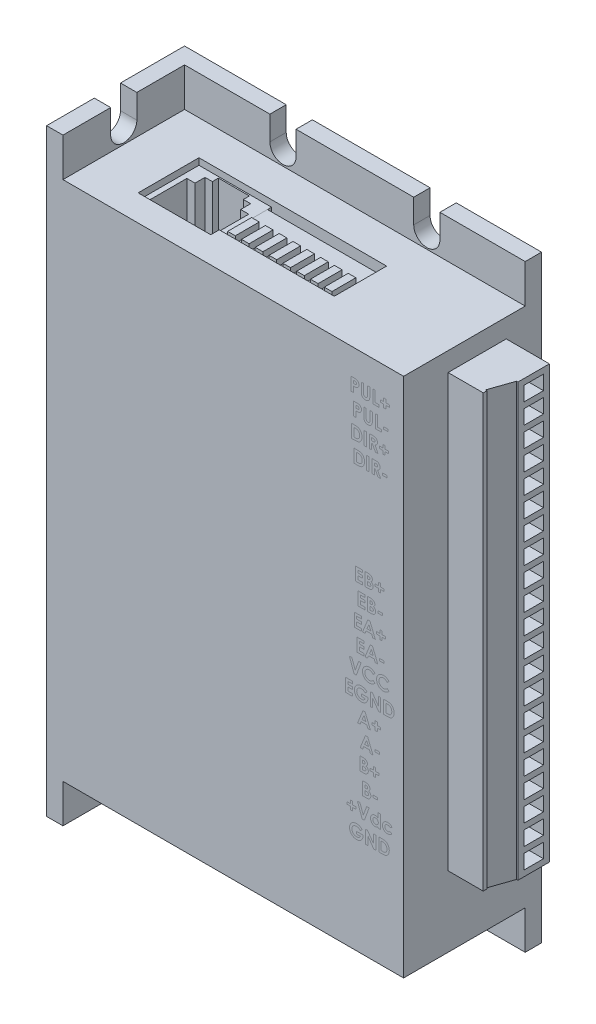
SolidWorks part; units mm, degrees
ref_plane "Front Plane" through (0, 0, 0) normal (0, 0, 1) x (1, 0, 0)
ref_plane "Top Plane" through (0, 0, 0) normal (0, 1, 0) x (1, 0, 0)
ref_plane "Right Plane" through (0, 0, 0) normal (1, 0, 0) x (0, 0, -1)
sketch "Sketch1" plane through (0, 0, 0) normal (0, 0, 1) x (1, 0, 0)
  line L1 (-34.671, 58.1025) -> (34.671, 58.1025)
  line L2 (-34.671, 58.1025) -> (-34.671, -58.1025)
  line L3 (-34.671, -58.1025) -> (34.671, -58.1025)
  line L4 (34.671, 58.1025) -> (34.671, -58.1025)
  line L5 (-34.671, 58.1025) -> (34.671, -58.1025) construction
  line L6 (-34.671, -58.1025) -> (34.671, 58.1025) construction
  point P0 (0, 0)
  dimension "D1" = 69.342
  dimension "D2" = 116.205
extrude "Boss-Extrude1" add sketch "Sketch1" along normal blind 26.797
sketch "Sketch2" plane through (0, 0, 26.797) normal (0, 0, 1) x (1, 0, 0)
  line L0 (34.671, 58.1025) -> (-34.671, 58.1025) construction
  line L1 (-31.496, 58.1025) -> (34.671, 58.1025)
  line L2 (-31.496, 58.1025) -> (-31.496, 50.6095)
  line L3 (-31.496, 50.6095) -> (34.671, 50.6095)
  line L4 (34.671, 58.1025) -> (34.671, 50.6095)
  line L5 (34.671, -58.1025) -> (34.671, 58.1025) construction
  line L6 (-34.671, -58.1025) -> (34.671, -58.1025) construction
  line L7 (-31.496, -58.1025) -> (34.671, -58.1025)
  line L8 (-31.496, -58.1025) -> (-31.496, -50.6095)
  line L9 (-31.496, -50.6095) -> (34.671, -50.6095)
  line L10 (34.671, -58.1025) -> (34.671, -50.6095)
  line L11 (-34.671, 58.1025) -> (-34.671, -58.1025) construction
  dimension "D1" = 7.493
  dimension "D2" = 3.175
extrude "Cut-Extrude1" cut sketch "Sketch2" against normal offset from surface (23.622 mm away) 3.175 up to face at (0, 0, 0)
sketch "Sketch3" plane through (-31.496, 0, 0) normal (1, 0, 0) x (0, 0, -1)
  line L0 (-14.986, 62.7642) -> (-14.986, 53.4408) construction
  line L1 (-3.175, 58.1025) -> (-26.797, 58.1025) construction
  line L2 (-12.446, 62.7642) -> (-12.446, 53.4408)
  line L3 (-17.526, 62.7642) -> (-17.526, 53.4408)
  line L4 (0, 0) -> (-26.797, 0) construction
  line L5 (-26.797, -50.6095) -> (-26.797, 50.6095) construction
  line L6 (-14.986, -62.7642) -> (-14.986, -53.4408) construction
  line L7 (-12.446, -62.7642) -> (-12.446, -53.4408)
  line L8 (-17.526, -62.7642) -> (-17.526, -53.4408)
  arc A0 (-12.446, 62.7642) -> (-17.526, 62.7642) centre (-14.986, 62.7642) ccw
  arc A1 (-17.526, 53.4408) -> (-12.446, 53.4408) centre (-14.986, 53.4408) ccw
  arc A2 (-12.446, -62.7642) -> (-17.526, -62.7642) centre (-14.986, -62.7642) cw
  arc A3 (-17.526, -53.4408) -> (-12.446, -53.4408) centre (-14.986, -53.4408) cw
  point P4 (-14.986, 58.1025)
  point P16 (-14.986, -58.1025)
  dimension "D1" = 5.08
  dimension "D2" = 4.6617
extrude "Cut-Extrude2" cut sketch "Sketch3" against normal through all
sketch "Sketch4" plane through (0, 0, 3.175) normal (0, 0, 1) x (1, 0, 0)
  line L0 (15.5575, 58.1025) -> (-12.3825, 58.1025) construction
  line L1 (-31.496, 58.1025) -> (34.671, 58.1025) construction
  line L2 (-12.3825, 62.7634) -> (-12.3825, 53.4416) construction
  line L3 (-9.8425, 62.7634) -> (-9.8425, 53.4416)
  line L4 (-14.9225, 62.7634) -> (-14.9225, 53.4416)
  line L5 (1.5875, 58.1025) -> (1.5875, -58.1025) construction
  line L6 (34.671, -58.1025) -> (-31.496, -58.1025) construction
  line L7 (1.5875, 0) -> (34.671, 0) construction
  line L8 (34.671, -50.6095) -> (34.671, 50.6095) construction
  line L9 (15.5575, 62.7634) -> (15.5575, 53.4416) construction
  line L10 (13.0175, 62.7634) -> (13.0175, 53.4416)
  line L11 (18.0975, 62.7634) -> (18.0975, 53.4416)
  line L12 (15.5575, -62.7634) -> (15.5575, -53.4416) construction
  line L13 (13.0175, -62.7634) -> (13.0175, -53.4416)
  line L14 (18.0975, -62.7634) -> (18.0975, -53.4416)
  line L15 (-12.3825, -62.7634) -> (-12.3825, -53.4416) construction
  line L16 (-9.8425, -62.7634) -> (-9.8425, -53.4416)
  line L17 (-14.9225, -62.7634) -> (-14.9225, -53.4416)
  arc A0 (-9.8425, 62.7634) -> (-14.9225, 62.7634) centre (-12.3825, 62.7634) ccw
  arc A1 (-14.9225, 53.4416) -> (-9.8425, 53.4416) centre (-12.3825, 53.4416) ccw
  arc A2 (13.0175, 62.7634) -> (18.0975, 62.7634) centre (15.5575, 62.7634) cw
  arc A3 (18.0975, 53.4416) -> (13.0175, 53.4416) centre (15.5575, 53.4416) cw
  arc A4 (13.0175, -62.7634) -> (18.0975, -62.7634) centre (15.5575, -62.7634) ccw
  arc A5 (18.0975, -53.4416) -> (13.0175, -53.4416) centre (15.5575, -53.4416) ccw
  arc A6 (-9.8425, -62.7634) -> (-14.9225, -62.7634) centre (-12.3825, -62.7634) cw
  arc A7 (-14.9225, -53.4416) -> (-9.8425, -53.4416) centre (-12.3825, -53.4416) cw
  point P5 (1.5875, 58.1025)
  point P7 (-12.3825, 58.1025)
  point P22 (15.5575, 58.1025)
  point P29 (15.5575, -58.1025)
  point P36 (-12.3825, -58.1025)
  dimension "D1" = 4.6609
  dimension "D2" = 5.08
  dimension "D3" = 27.94
extrude "Cut-Extrude3" cut sketch "Sketch4" against normal through all
sketch "Sketch5" plane through (0, 50.6095, 0) normal (0, 1, 0) x (1, 0, 0)
  line L0 (-34.671, -12.446) -> (-34.671, 0) construction
  line L1 (-21.971, -9.906) -> (-7.874, -9.906)
  line L2 (-21.971, -9.906) -> (-21.971, -21.717)
  line L3 (-21.971, -21.717) -> (-7.874, -21.717)
  line L4 (-7.874, -9.906) -> (-7.874, -21.717)
  line L5 (-31.496, -26.797) -> (34.671, -26.797) construction
  dimension "D1" = 12.7
  dimension "D2" = 11.811
  dimension "D3" = 14.097
  dimension "D4" = 5.08
extrude "Cut-Extrude4" cut sketch "Sketch5" against normal blind 12.7
sketch "Sketch6" plane through (0, 50.6095, 0) normal (0, 1, 0) x (1, 0, 0)
  line L1 (-7.874, -9.906) -> (14.478, -9.906)
  line L2 (-7.874, -9.906) -> (-7.874, -20.066)
  line L3 (-7.874, -20.066) -> (14.478, -20.066)
  line L4 (14.478, -9.906) -> (14.478, -20.066)
  dimension "D1" = 22.352
  dimension "D2" = 10.16
extrude "Cut-Extrude5" cut sketch "Sketch6" against normal blind 2.54
sketch "Sketch7" plane through (0, 48.0695, 0) normal (0, 1, 0) x (1, 0, 0)
  line L0 (-7.874, -21.717) -> (-7.874, -9.906) construction
  line L1 (-7.874, -10.7001) -> (14.478, -10.7001)
  line L2 (-7.874, -10.7001) -> (-7.874, -20.066)
  line L3 (-7.874, -20.066) -> (14.478, -20.066)
  line L4 (14.478, -10.7001) -> (14.478, -20.066)
extrude "Boss-Extrude2" add sketch "Sketch7" along normal blind 1.27 separate body
sketch "Sketch8" plane through (0, 49.3395, 0) normal (0, 1, 0) x (1, 0, 0)
  line L0 (-4.119, -14.8518) -> (-2.6319, -14.8518)
  line L1 (-6.8001, -14.8518) -> (-5.313, -14.8518)
  line L2 (-6.8001, -14.8518) -> (-6.8001, -19.5049)
  line L3 (-6.8001, -19.5049) -> (-5.313, -19.5049)
  line L4 (-5.313, -14.8518) -> (-5.313, -19.5049)
  line L5 (-2.6319, -14.8518) -> (-2.6319, -19.5049)
  line L6 (-4.119, -19.5049) -> (-2.6319, -19.5049)
  line L7 (-4.119, -14.8518) -> (-4.119, -19.5049)
  line L8 (-1.4379, -14.8518) -> (0.0493, -14.8518)
  line L9 (0.0493, -14.8518) -> (0.0493, -19.5049)
  line L10 (-1.4379, -19.5049) -> (0.0493, -19.5049)
  line L11 (-1.4379, -14.8518) -> (-1.4379, -19.5049)
  line L12 (1.2432, -14.8518) -> (2.7304, -14.8518)
  line L13 (2.7304, -14.8518) -> (2.7304, -19.5049)
  line L14 (1.2432, -19.5049) -> (2.7304, -19.5049)
  line L15 (1.2432, -14.8518) -> (1.2432, -19.5049)
  line L16 (3.9244, -14.8518) -> (5.4115, -14.8518)
  line L17 (5.4115, -14.8518) -> (5.4115, -19.5049)
  line L18 (3.9244, -19.5049) -> (5.4115, -19.5049)
  line L19 (3.9244, -14.8518) -> (3.9244, -19.5049)
  line L20 (6.6055, -14.8518) -> (8.0926, -14.8518)
  line L21 (8.0926, -14.8518) -> (8.0926, -19.5049)
  line L22 (6.6055, -19.5049) -> (8.0926, -19.5049)
  line L23 (6.6055, -14.8518) -> (6.6055, -19.5049)
  line L24 (9.2866, -14.8518) -> (10.7738, -14.8518)
  line L25 (10.7738, -14.8518) -> (10.7738, -19.5049)
  line L26 (9.2866, -19.5049) -> (10.7738, -19.5049)
  line L27 (9.2866, -14.8518) -> (9.2866, -19.5049)
  line L28 (11.9677, -14.8518) -> (13.4549, -14.8518)
  line L29 (13.4549, -14.8518) -> (13.4549, -19.5049)
  line L30 (11.9677, -19.5049) -> (13.4549, -19.5049)
  line L31 (11.9677, -14.8518) -> (11.9677, -19.5049)
  dimension "D1" = 8
extrude "Boss-Extrude3" add sketch "Sketch8" along normal blind 1.27 separate body
sketch "Sketch9" plane through (0, 37.9095, 0) normal (0, 1, 0) x (1, 0, 0)
  line L0 (-14.9225, -9.906) -> (-14.9225, -21.717) construction
  line L1 (-7.874, -9.906) -> (-21.971, -9.906) construction
  line L2 (-21.971, -21.717) -> (-7.874, -21.717) construction
  line L3 (-8.9055, -20.8461) -> (-20.9395, -20.8461)
  line L4 (-20.9395, -20.8461) -> (-20.9395, -13.2906)
  line L5 (-20.9395, -13.2906) -> (-19.3565, -13.2906)
  line L6 (-19.3565, -13.2906) -> (-19.3565, -11.3477)
  line L7 (-19.3565, -11.3477) -> (-17.931, -11.3477)
  line L8 (-17.931, -11.3477) -> (-17.931, -10.169)
  line L9 (-17.931, -10.169) -> (-11.914, -10.169)
  line L10 (-8.9055, -20.8461) -> (-8.9055, -13.2906)
  line L11 (-8.9055, -13.2906) -> (-10.4885, -13.2906)
  line L12 (-10.4885, -13.2906) -> (-10.4885, -11.3477)
  line L13 (-10.4885, -11.3477) -> (-11.914, -11.3477)
  line L14 (-11.914, -11.3477) -> (-11.914, -10.169)
  line L19 (-21.971, -9.906) -> (-21.971, -21.717)
  line L20 (-21.971, -21.717) -> (-7.874, -21.717)
  line L21 (-7.874, -21.717) -> (-7.874, -9.906)
  line L22 (-7.874, -9.906) -> (-21.971, -9.906)
  line L23 (-21.971, -9.906) -> (-21.971, -21.717)
  line L24 (-21.971, -21.717) -> (-7.874, -21.717)
  line L25 (-7.874, -21.717) -> (-7.874, -9.906)
  line L26 (-7.874, -9.906) -> (-21.971, -9.906)
  point P15 (-14.9225, -20.8461)
  point P20 (-14.9225, -10.169)
  dimension "D1" = 0
extrude "Boss-Extrude4" add sketch "Sketch9" along normal offset from surface (11.43 mm away) 1.27 separate body up to face at (-5.1223, 50.6095, 17.2297)
sketch "Sketch10" plane through (34.671, 0, 0) normal (1, 0, 0) x (0, 0, -1)
  line L0 (0, -58.1025) -> (0, 58.1025) construction
  line L1 (-18.161, 46.9265) -> (-6.858, 46.9265)
  line L2 (-18.161, 46.9265) -> (-18.161, -36.8935)
  line L3 (-18.161, -36.8935) -> (-6.858, -36.8935)
  line L4 (-6.858, 46.9265) -> (-6.858, -36.8935)
  line L5 (-3.175, 58.1025) -> (-12.446, 58.1025) construction
  dimension "D1" = 83.82
  dimension "D2" = 11.303
  dimension "D3" = 6.858
  dimension "D4" = 11.176
extrude "Cut-Extrude6" cut sketch "Sketch10" against normal blind 5.08
sketch "Sketch11" plane through (0, 46.9265, 0) normal (0, -1, 0) x (1, 0, 0)
  line L0 (34.671, 18.161) -> (41.5074, 18.161)
  line L1 (41.5074, 18.161) -> (41.5074, 17.4431)
  line L2 (41.5074, 17.4431) -> (41.2303, 17.4431)
  line L3 (41.2303, 17.4431) -> (42.7863, 12.954)
  line L4 (42.7863, 12.954) -> (43.053, 12.954)
  line L5 (43.053, 12.954) -> (43.053, 6.858)
  line L6 (43.053, 6.858) -> (34.671, 6.858)
  line L7 (34.671, 6.858) -> (34.671, 18.161)
  dimension "D1" = 8.382
  dimension "D2" = 6.096
extrude "Boss-Extrude5" add sketch "Sketch11" along normal up to surface (83.82 mm away) separate body up to face at (32.131, -36.8935, 12.5095)
sketch "Sketch12" plane through (43.053, 0, 0) normal (1, 0, 0) x (0, 0, -1)
  line L0 (-11.811, 41.8465) -> (-8.001, 41.8465)
  line L1 (-11.811, 45.7835) -> (-8.001, 45.7835)
  line L2 (-11.811, 45.7835) -> (-11.811, 42.9895)
  line L3 (-11.811, 42.9895) -> (-8.001, 42.9895)
  line L4 (-8.001, 45.7835) -> (-8.001, 42.9895)
  line L5 (-11.811, 41.8465) -> (-11.811, 39.0525)
  line L6 (-11.811, 39.0525) -> (-8.001, 39.0525)
  line L7 (-8.001, 41.8465) -> (-8.001, 39.0525)
  line L8 (-11.811, 37.9095) -> (-8.001, 37.9095)
  line L9 (-11.811, 37.9095) -> (-11.811, 35.1155)
  line L10 (-11.811, 35.1155) -> (-8.001, 35.1155)
  line L11 (-8.001, 37.9095) -> (-8.001, 35.1155)
  line L12 (-11.811, 33.9725) -> (-8.001, 33.9725)
  line L13 (-11.811, 33.9725) -> (-11.811, 31.1785)
  line L14 (-11.811, 31.1785) -> (-8.001, 31.1785)
  line L15 (-8.001, 33.9725) -> (-8.001, 31.1785)
  line L16 (-11.811, 30.0355) -> (-8.001, 30.0355)
  line L17 (-11.811, 30.0355) -> (-11.811, 27.2415)
  line L18 (-11.811, 27.2415) -> (-8.001, 27.2415)
  line L19 (-8.001, 30.0355) -> (-8.001, 27.2415)
  line L20 (-11.811, 26.0985) -> (-8.001, 26.0985)
  line L21 (-11.811, 26.0985) -> (-11.811, 23.3045)
  line L22 (-11.811, 23.3045) -> (-8.001, 23.3045)
  line L23 (-8.001, 26.0985) -> (-8.001, 23.3045)
  line L24 (-11.811, 22.1615) -> (-8.001, 22.1615)
  line L25 (-11.811, 22.1615) -> (-11.811, 19.3675)
  line L26 (-11.811, 19.3675) -> (-8.001, 19.3675)
  line L27 (-8.001, 22.1615) -> (-8.001, 19.3675)
  line L28 (-11.811, 18.2245) -> (-8.001, 18.2245)
  line L29 (-11.811, 18.2245) -> (-11.811, 15.4305)
  line L30 (-11.811, 15.4305) -> (-8.001, 15.4305)
  line L31 (-8.001, 18.2245) -> (-8.001, 15.4305)
  line L32 (-11.811, 14.2875) -> (-8.001, 14.2875)
  line L33 (-11.811, 14.2875) -> (-11.811, 11.4935)
  line L34 (-11.811, 11.4935) -> (-8.001, 11.4935)
  line L35 (-8.001, 14.2875) -> (-8.001, 11.4935)
  line L36 (-11.811, 10.3505) -> (-8.001, 10.3505)
  line L37 (-11.811, 10.3505) -> (-11.811, 7.5565)
  line L38 (-11.811, 7.5565) -> (-8.001, 7.5565)
  line L39 (-8.001, 10.3505) -> (-8.001, 7.5565)
  line L40 (-11.811, 6.4135) -> (-8.001, 6.4135)
  line L41 (-11.811, 6.4135) -> (-11.811, 3.6195)
  line L42 (-11.811, 3.6195) -> (-8.001, 3.6195)
  line L43 (-8.001, 6.4135) -> (-8.001, 3.6195)
  line L44 (-11.811, 2.4765) -> (-8.001, 2.4765)
  line L45 (-11.811, 2.4765) -> (-11.811, -0.3175)
  line L46 (-11.811, -0.3175) -> (-8.001, -0.3175)
  line L47 (-8.001, 2.4765) -> (-8.001, -0.3175)
  line L48 (-11.811, -1.4605) -> (-8.001, -1.4605)
  line L49 (-11.811, -1.4605) -> (-11.811, -4.2545)
  line L50 (-11.811, -4.2545) -> (-8.001, -4.2545)
  line L51 (-8.001, -1.4605) -> (-8.001, -4.2545)
  line L52 (-11.811, -5.3975) -> (-8.001, -5.3975)
  line L53 (-11.811, -5.3975) -> (-11.811, -8.1915)
  line L54 (-11.811, -8.1915) -> (-8.001, -8.1915)
  line L55 (-8.001, -5.3975) -> (-8.001, -8.1915)
  line L56 (-11.811, -9.3345) -> (-8.001, -9.3345)
  line L57 (-11.811, -9.3345) -> (-11.811, -12.1285)
  line L58 (-11.811, -12.1285) -> (-8.001, -12.1285)
  line L59 (-8.001, -9.3345) -> (-8.001, -12.1285)
  line L60 (-11.811, -13.2715) -> (-8.001, -13.2715)
  line L61 (-11.811, -13.2715) -> (-11.811, -16.0655)
  line L62 (-11.811, -16.0655) -> (-8.001, -16.0655)
  line L63 (-8.001, -13.2715) -> (-8.001, -16.0655)
  line L64 (-11.811, -17.2085) -> (-8.001, -17.2085)
  line L65 (-11.811, -17.2085) -> (-11.811, -20.0025)
  line L66 (-11.811, -20.0025) -> (-8.001, -20.0025)
  line L67 (-8.001, -17.2085) -> (-8.001, -20.0025)
  line L68 (-11.811, -21.1455) -> (-8.001, -21.1455)
  line L69 (-11.811, -21.1455) -> (-11.811, -23.9395)
  line L70 (-11.811, -23.9395) -> (-8.001, -23.9395)
  line L71 (-8.001, -21.1455) -> (-8.001, -23.9395)
  line L72 (-11.811, -25.0825) -> (-8.001, -25.0825)
  line L73 (-11.811, -25.0825) -> (-11.811, -27.8765)
  line L74 (-11.811, -27.8765) -> (-8.001, -27.8765)
  line L75 (-8.001, -25.0825) -> (-8.001, -27.8765)
  line L76 (-11.811, -29.0195) -> (-8.001, -29.0195)
  line L77 (-11.811, -29.0195) -> (-11.811, -31.8135)
  line L78 (-11.811, -31.8135) -> (-8.001, -31.8135)
  line L79 (-8.001, -29.0195) -> (-8.001, -31.8135)
  line L80 (-11.811, -32.9565) -> (-8.001, -32.9565)
  line L81 (-11.811, -32.9565) -> (-11.811, -35.7505)
  line L82 (-11.811, -35.7505) -> (-8.001, -35.7505)
  line L83 (-8.001, -32.9565) -> (-8.001, -35.7505)
  line L84 (-9.906, 45.7835) -> (-9.906, 46.9265) construction
  line L85 (-6.858, 46.9265) -> (-12.954, 46.9265) construction
  line L86 (-11.811, 44.3865) -> (-12.954, 44.3865) construction
  line L87 (-12.954, -36.8935) -> (-12.954, 46.9265) construction
  line L88 (-9.906, 42.9895) -> (-9.906, 41.8465) construction
  line L89 (-8.001, 44.3865) -> (-6.858, 44.3865) construction
  line L90 (-6.858, -36.8935) -> (-6.858, 46.9265) construction
  line L91 (-9.906, -35.7505) -> (-9.906, -36.8935) construction
  line L92 (-6.858, -36.8935) -> (-12.954, -36.8935) construction
  dimension "D2" = 2.794
  dimension "D1" = 21
extrude "Cut-Extrude7" cut sketch "Sketch12" against normal blind 5.08
sketch "Sketch13" plane through (0, 0, 26.797) normal (0, 0, 1) x (1, 0, 0)
  line L1 (37.973, 42.9895) -> (18.1191, 42.9895) construction
  line L3 (37.973, 39.0525) -> (18.1191, 39.0525) construction
  line L4 (37.973, 35.1155) -> (18.1191, 35.1155) construction
  line L5 (37.973, 31.1785) -> (18.1191, 31.1785) construction
  line L6 (43.053, 42.9895) -> (43.053, 45.7835)
  line L7 (43.053, 45.7835) -> (37.973, 45.7835)
  line L8 (37.973, 45.7835) -> (37.973, 42.9895)
  line L9 (37.973, 42.9895) -> (43.053, 42.9895)
  line L10 (43.053, 42.9895) -> (43.053, 45.7835) construction
  line L11 (43.053, 45.7835) -> (37.973, 45.7835) construction
  line L12 (37.973, 45.7835) -> (37.973, 42.9895) construction
  line L13 (37.973, 42.9895) -> (43.053, 42.9895) construction
  line L14 (43.053, 39.0525) -> (43.053, 41.8465)
  line L15 (43.053, 41.8465) -> (37.973, 41.8465)
  line L16 (37.973, 41.8465) -> (37.973, 39.0525)
  line L17 (37.973, 39.0525) -> (43.053, 39.0525)
  line L18 (43.053, 39.0525) -> (43.053, 41.8465) construction
  line L19 (43.053, 41.8465) -> (37.973, 41.8465) construction
  line L20 (37.973, 41.8465) -> (37.973, 39.0525) construction
  line L21 (37.973, 39.0525) -> (43.053, 39.0525) construction
  line L22 (43.053, 35.1155) -> (43.053, 37.9095)
  line L23 (43.053, 37.9095) -> (37.973, 37.9095)
  line L24 (37.973, 37.9095) -> (37.973, 35.1155)
  line L25 (37.973, 35.1155) -> (43.053, 35.1155)
  line L26 (43.053, 35.1155) -> (43.053, 37.9095) construction
  line L27 (43.053, 37.9095) -> (37.973, 37.9095) construction
  line L28 (37.973, 37.9095) -> (37.973, 35.1155) construction
  line L29 (37.973, 35.1155) -> (43.053, 35.1155) construction
  line L30 (43.053, 31.1785) -> (43.053, 33.9725)
  line L31 (43.053, 33.9725) -> (37.973, 33.9725)
  line L32 (37.973, 33.9725) -> (37.973, 31.1785)
  line L33 (37.973, 31.1785) -> (43.053, 31.1785)
  line L34 (43.053, 31.1785) -> (43.053, 33.9725) construction
  line L35 (43.053, 33.9725) -> (37.973, 33.9725) construction
  line L36 (37.973, 33.9725) -> (37.973, 31.1785) construction
  line L37 (37.973, 31.1785) -> (43.053, 31.1785) construction
  line L38 (43.053, 27.2415) -> (43.053, 30.0355)
  line L39 (43.053, 30.0355) -> (37.973, 30.0355)
  line L40 (37.973, 30.0355) -> (37.973, 27.2415)
  line L41 (37.973, 27.2415) -> (43.053, 27.2415)
  line L42 (43.053, 27.2415) -> (43.053, 30.0355) construction
  line L43 (43.053, 30.0355) -> (37.973, 30.0355) construction
  line L44 (37.973, 30.0355) -> (37.973, 27.2415) construction
  line L45 (37.973, 27.2415) -> (43.053, 27.2415) construction
  line L46 (43.053, 23.3045) -> (43.053, 26.0985)
  line L47 (43.053, 26.0985) -> (37.973, 26.0985)
  line L48 (37.973, 26.0985) -> (37.973, 23.3045)
  line L49 (37.973, 23.3045) -> (43.053, 23.3045)
  line L50 (43.053, 23.3045) -> (43.053, 26.0985) construction
  line L51 (43.053, 26.0985) -> (37.973, 26.0985) construction
  line L52 (37.973, 26.0985) -> (37.973, 23.3045) construction
  line L53 (37.973, 23.3045) -> (43.053, 23.3045) construction
  line L54 (43.053, 19.3675) -> (43.053, 22.1615)
  line L55 (43.053, 22.1615) -> (37.973, 22.1615)
  line L56 (37.973, 22.1615) -> (37.973, 19.3675)
  line L57 (37.973, 19.3675) -> (43.053, 19.3675)
  line L58 (43.053, 19.3675) -> (43.053, 22.1615) construction
  line L59 (43.053, 22.1615) -> (37.973, 22.1615) construction
  line L60 (37.973, 22.1615) -> (37.973, 19.3675) construction
  line L61 (37.973, 19.3675) -> (43.053, 19.3675) construction
  line L62 (43.053, 15.4305) -> (43.053, 18.2245)
  line L63 (43.053, 18.2245) -> (37.973, 18.2245)
  line L64 (37.973, 18.2245) -> (37.973, 15.4305)
  line L65 (37.973, 15.4305) -> (43.053, 15.4305)
  line L66 (43.053, 15.4305) -> (43.053, 18.2245) construction
  line L67 (43.053, 18.2245) -> (37.973, 18.2245) construction
  line L68 (37.973, 18.2245) -> (37.973, 15.4305) construction
  line L69 (37.973, 15.4305) -> (43.053, 15.4305) construction
  line L70 (43.053, 11.4935) -> (43.053, 14.2875)
  line L71 (43.053, 14.2875) -> (37.973, 14.2875)
  line L72 (37.973, 14.2875) -> (37.973, 11.4935)
  line L73 (37.973, 11.4935) -> (43.053, 11.4935)
  line L74 (43.053, 11.4935) -> (43.053, 14.2875) construction
  line L75 (43.053, 14.2875) -> (37.973, 14.2875) construction
  line L76 (37.973, 14.2875) -> (37.973, 11.4935) construction
  line L77 (37.973, 11.4935) -> (43.053, 11.4935) construction
  line L78 (43.053, 7.5565) -> (43.053, 10.3505)
  line L79 (43.053, 10.3505) -> (37.973, 10.3505)
  line L80 (37.973, 10.3505) -> (37.973, 7.5565)
  line L81 (37.973, 7.5565) -> (43.053, 7.5565)
  line L82 (43.053, 7.5565) -> (43.053, 10.3505) construction
  line L83 (43.053, 10.3505) -> (37.973, 10.3505) construction
  line L84 (37.973, 10.3505) -> (37.973, 7.5565) construction
  line L85 (37.973, 7.5565) -> (43.053, 7.5565) construction
  line L86 (43.053, 3.6195) -> (43.053, 6.4135)
  line L87 (43.053, 6.4135) -> (37.973, 6.4135)
  line L88 (37.973, 6.4135) -> (37.973, 3.6195)
  line L89 (37.973, 3.6195) -> (43.053, 3.6195)
  line L90 (43.053, 3.6195) -> (43.053, 6.4135) construction
  line L91 (43.053, 6.4135) -> (37.973, 6.4135) construction
  line L92 (37.973, 6.4135) -> (37.973, 3.6195) construction
  line L93 (37.973, 3.6195) -> (43.053, 3.6195) construction
  line L94 (43.053, -0.3175) -> (43.053, 2.4765)
  line L95 (43.053, 2.4765) -> (37.973, 2.4765)
  line L96 (37.973, 2.4765) -> (37.973, -0.3175)
  line L97 (37.973, -0.3175) -> (43.053, -0.3175)
  line L98 (43.053, -0.3175) -> (43.053, 2.4765) construction
  line L99 (43.053, 2.4765) -> (37.973, 2.4765) construction
  line L100 (37.973, 2.4765) -> (37.973, -0.3175) construction
  line L101 (37.973, -0.3175) -> (43.053, -0.3175) construction
  line L102 (43.053, -4.2545) -> (43.053, -1.4605)
  line L103 (43.053, -1.4605) -> (37.973, -1.4605)
  line L104 (37.973, -1.4605) -> (37.973, -4.2545)
  line L105 (37.973, -4.2545) -> (43.053, -4.2545)
  line L106 (43.053, -4.2545) -> (43.053, -1.4605) construction
  line L107 (43.053, -1.4605) -> (37.973, -1.4605) construction
  line L108 (37.973, -1.4605) -> (37.973, -4.2545) construction
  line L109 (37.973, -4.2545) -> (43.053, -4.2545) construction
  line L110 (43.053, -8.1915) -> (43.053, -5.3975)
  line L111 (43.053, -5.3975) -> (37.973, -5.3975)
  line L112 (37.973, -5.3975) -> (37.973, -8.1915)
  line L113 (37.973, -8.1915) -> (43.053, -8.1915)
  line L114 (43.053, -8.1915) -> (43.053, -5.3975) construction
  line L115 (43.053, -5.3975) -> (37.973, -5.3975) construction
  line L116 (37.973, -5.3975) -> (37.973, -8.1915) construction
  line L117 (37.973, -8.1915) -> (43.053, -8.1915) construction
  line L118 (43.053, -12.1285) -> (43.053, -9.3345)
  line L119 (43.053, -9.3345) -> (37.973, -9.3345)
  line L120 (37.973, -9.3345) -> (37.973, -12.1285)
  line L121 (37.973, -12.1285) -> (43.053, -12.1285)
  line L122 (43.053, -12.1285) -> (43.053, -9.3345) construction
  line L123 (43.053, -9.3345) -> (37.973, -9.3345) construction
  line L124 (37.973, -9.3345) -> (37.973, -12.1285) construction
  line L125 (37.973, -12.1285) -> (43.053, -12.1285) construction
  line L126 (43.053, -16.0655) -> (43.053, -13.2715)
  line L127 (43.053, -13.2715) -> (37.973, -13.2715)
  line L128 (37.973, -13.2715) -> (37.973, -16.0655)
  line L129 (37.973, -16.0655) -> (43.053, -16.0655)
  line L130 (43.053, -16.0655) -> (43.053, -13.2715) construction
  line L131 (43.053, -13.2715) -> (37.973, -13.2715) construction
  line L132 (37.973, -13.2715) -> (37.973, -16.0655) construction
  line L133 (37.973, -16.0655) -> (43.053, -16.0655) construction
  line L134 (43.053, -20.0025) -> (43.053, -17.2085)
  line L135 (43.053, -17.2085) -> (37.973, -17.2085)
  line L136 (37.973, -17.2085) -> (37.973, -20.0025)
  line L137 (37.973, -20.0025) -> (43.053, -20.0025)
  line L138 (43.053, -20.0025) -> (43.053, -17.2085) construction
  line L139 (43.053, -17.2085) -> (37.973, -17.2085) construction
  line L140 (37.973, -17.2085) -> (37.973, -20.0025) construction
  line L141 (37.973, -20.0025) -> (43.053, -20.0025) construction
  line L142 (43.053, -23.9395) -> (43.053, -21.1455)
  line L143 (43.053, -21.1455) -> (37.973, -21.1455)
  line L144 (37.973, -21.1455) -> (37.973, -23.9395)
  line L145 (37.973, -23.9395) -> (43.053, -23.9395)
  line L146 (43.053, -23.9395) -> (43.053, -21.1455) construction
  line L147 (43.053, -21.1455) -> (37.973, -21.1455) construction
  line L148 (37.973, -21.1455) -> (37.973, -23.9395) construction
  line L149 (37.973, -23.9395) -> (43.053, -23.9395) construction
  line L150 (43.053, -31.8135) -> (43.053, -29.0195)
  line L151 (43.053, -29.0195) -> (37.973, -29.0195)
  line L152 (37.973, -29.0195) -> (37.973, -31.8135)
  line L153 (37.973, -31.8135) -> (43.053, -31.8135)
  line L154 (43.053, -31.8135) -> (43.053, -29.0195) construction
  line L155 (43.053, -29.0195) -> (37.973, -29.0195) construction
  line L156 (37.973, -29.0195) -> (37.973, -31.8135) construction
  line L157 (37.973, -31.8135) -> (43.053, -31.8135) construction
  line L158 (43.053, -27.8765) -> (43.053, -25.0825)
  line L159 (43.053, -25.0825) -> (37.973, -25.0825)
  line L160 (37.973, -25.0825) -> (37.973, -27.8765)
  line L161 (37.973, -27.8765) -> (43.053, -27.8765)
  line L162 (43.053, -27.8765) -> (43.053, -25.0825) construction
  line L163 (43.053, -25.0825) -> (37.973, -25.0825) construction
  line L164 (37.973, -25.0825) -> (37.973, -27.8765) construction
  line L165 (37.973, -27.8765) -> (43.053, -27.8765) construction
  line L166 (43.053, -35.7505) -> (43.053, -32.9565)
  line L167 (43.053, -32.9565) -> (37.973, -32.9565)
  line L168 (37.973, -32.9565) -> (37.973, -35.7505)
  line L169 (37.973, -35.7505) -> (43.053, -35.7505)
  line L170 (43.053, -35.7505) -> (43.053, -32.9565) construction
  line L171 (43.053, -32.9565) -> (37.973, -32.9565) construction
  line L172 (37.973, -32.9565) -> (37.973, -35.7505) construction
  line L173 (37.973, -35.7505) -> (43.053, -35.7505) construction
  line L174 (37.973, 27.2415) -> (18.1191, 27.2415) construction
  line L175 (37.973, 23.3045) -> (18.1191, 23.3045) construction
  line L176 (37.973, 19.3675) -> (18.1191, 19.3675) construction
  line L177 (37.973, 15.4305) -> (18.1191, 15.4305) construction
  line L178 (37.973, 11.4935) -> (18.1191, 11.4935) construction
  line L179 (37.973, 7.5565) -> (18.1191, 7.5565) construction
  line L180 (37.973, 3.6195) -> (18.1191, 3.6195) construction
  line L181 (37.973, -0.3175) -> (18.1191, -0.3175) construction
  line L182 (37.973, -4.2545) -> (18.1191, -4.2545) construction
  line L183 (37.973, -8.1915) -> (18.1191, -8.1915) construction
  line L184 (37.973, -12.1285) -> (18.1191, -12.1285) construction
  line L185 (37.973, -16.0655) -> (18.1191, -16.0655) construction
  line L186 (37.973, -20.0025) -> (18.1191, -20.0025) construction
  line L187 (37.973, -23.9395) -> (18.1191, -23.9395) construction
  line L188 (37.973, -27.8765) -> (18.1191, -27.8765) construction
  line L189 (37.973, -31.8135) -> (18.1191, -31.8135) construction
  line L190 (37.973, -35.7505) -> (18.1191, -35.7505) construction
  text T0 "<b>PUL+</b>" font "Century Gothic" height 2.54
  text T1 "<b>PUL-</b>" font "Century Gothic" height 2.54
  text T2 "<b>DIR+</b>" font "Century Gothic" height 2.54
  text T3 "<b>DIR-</b>" font "Century Gothic" height 2.54
  text T4 "<b>GND</b>" font "Century Gothic" height 2.54
  text T5 "<b>+Vdc</b>" font "Century Gothic" height 2.54
  text T6 "<b>B-</b>" font "Century Gothic" height 2.54
  text T7 "<b>B+</b>" font "Century Gothic" height 2.54
  text T8 "<b>A-</b>" font "Century Gothic" height 2.54
  text T9 "<b>A+</b>" font "Century Gothic" height 2.54
  text T10 "<b>EGND</b>" font "Century Gothic" height 2.54
  text T11 "<b>VCC</b>" font "Century Gothic" height 2.54
  text T12 "<b>EA-</b>" font "Century Gothic" height 2.54
  text T13 "<b>EA+</b>" font "Century Gothic" height 2.54
  text T14 "<b>EB-</b>" font "Century Gothic" height 2.54
  text T15 "<b>EB+</b>" font "Century Gothic" height 2.54
  dimension "D1" = 0
  dimension "D2" = 0
  dimension "D3" = 0
  dimension "D4" = 0
  dimension "D5" = 0
  dimension "D6" = 0
  dimension "D7" = 0
  dimension "D8" = 0
  dimension "D9" = 0
  dimension "D10" = 0
  dimension "D11" = 0
  dimension "D12" = 0
  dimension "D13" = 0
  dimension "D14" = 0
  dimension "D15" = 0
  dimension "D16" = 0
  dimension "D17" = 0
  dimension "D18" = 0
  dimension "D19" = 0
  dimension "D20" = 0
  dimension "D21" = 0
  dimension "D22" = 21
split line "Split Line1"
